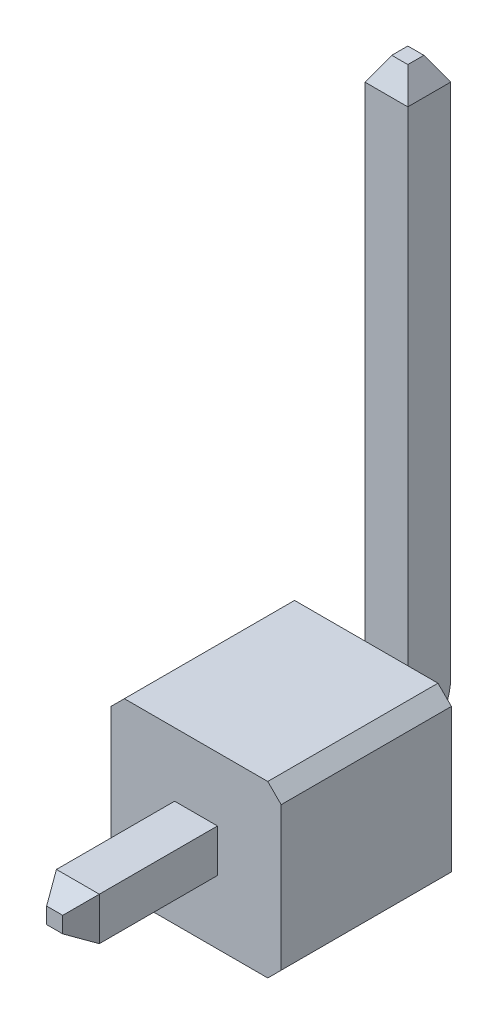
SolidWorks part; units mm, degrees
ref_plane "Front" through (0, 0, 0) normal (0, 0, 1) x (1, 0, 0)
ref_plane "Top" through (0, 0, 0) normal (0, 1, 0) x (1, 0, 0)
ref_plane "Right" through (0, 0, 0) normal (1, 0, 0) x (0, 0, -1)
sketch "Эскиз1" plane through (0, 0, 0) normal (1, 0, 0) x (0, 0, -1)
  line L0 (0, 0) -> (0, -8.04)
  line L1 (-0.5, -8.54) -> (-5.27, -8.54)
  arc A0 (0, -8.04) -> (-0.5, -8.54) centre (-0.5, -8.04) cw
  dimension "D1" = 0.5
  dimension "D2" = 0.5
  dimension "D3" = 8.54
  dimension "D4" = 5.27
sketch "Эскиз2" plane through (0, 0, 0) normal (0, 1, 0) x (1, 0, 0)
  line L1 (-0.32, 0.32) -> (0.32, 0.32)
  line L2 (-0.32, 0.32) -> (-0.32, -0.32)
  line L3 (-0.32, -0.32) -> (0.32, -0.32)
  line L4 (0.32, 0.32) -> (0.32, -0.32)
  line L5 (-0.32, 0.32) -> (0.32, -0.32) construction
  line L6 (-0.32, -0.32) -> (0.32, 0.32) construction
  point P0 (0, 0)
  dimension "D1" = 0.64
  dimension "D2" = 0.64
sweep "По траектории1" add profiles "Эскиз2" path "Эскиз1"
chamfer "Фаска1" distance 0.2 angle 60 4 edges at (0.32, -8.54, 5.27) (-0.32, -8.54, 5.27) (0, -8.22, 5.27) (0, -8.86, 5.27)
chamfer "Фаска2" distance 0.2 angle 60 4 edges at (0.32, 0, 0) (-0.32, 0, 0) (0, 0, 0.32) (0, 0, -0.32)
ref_plane "Плоскость1" through (0, 0, 0.62) normal (0, 0, 1) x (1, 0, 0)
sketch "Эскиз3" plane through (0, 0, 0.62) normal (0, 0, 1) x (1, 0, 0)
  line L1 (-1.27, -7.27) -> (1.27, -7.27)
  line L2 (-1.27, -7.27) -> (-1.27, -9.81)
  line L3 (-1.27, -9.81) -> (1.27, -9.81)
  line L4 (1.27, -7.27) -> (1.27, -9.81)
  line L5 (-1.27, -7.27) -> (1.27, -9.81) construction
  line L6 (-1.27, -9.81) -> (1.27, -7.27) construction
  point P0 (0, -8.54)
  point P8 (-2.3837, -4.5549)
  dimension "D1" = 2.54
  dimension "D2" = 2.54
  dimension "D3" = 0
  dimension "D4" = 8.54
extrude "Бобышка-Вытянуть1" add sketch "Эскиз3" along normal blind 2.54
chamfer "Фаска3" distance 0.2 angle 45 4 edges at (-1.27, -7.27, 1.89) (1.27, -7.27, 1.89) (1.27, -9.81, 1.89) (-1.27, -9.81, 1.89)
